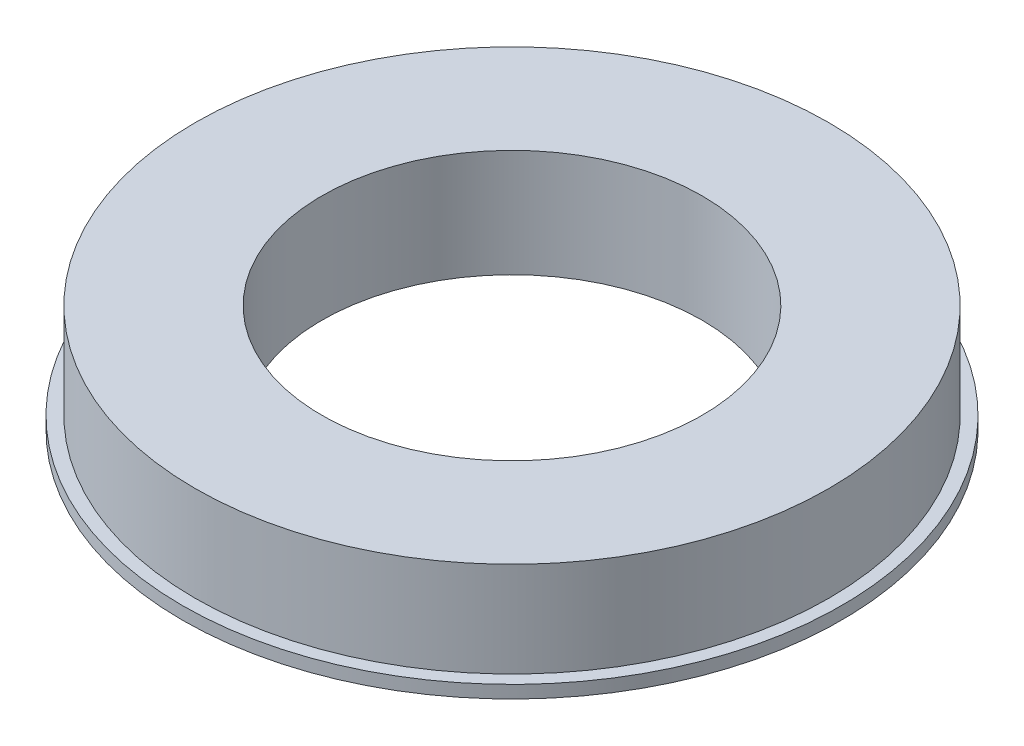
SolidWorks part; units mm, degrees
ref_plane "Front Plane" through (0, 0, 0) normal (0, 0, 1) x (1, 0, 0)
ref_plane "Top Plane" through (0, 0, 0) normal (0, 1, 0) x (1, 0, 0)
ref_plane "Right Plane" through (0, 0, 0) normal (1, 0, 0) x (0, 0, -1)
sketch "Sketch1" plane through (0, 0, 0) normal (0, 1, 0) x (1, 0, 0)
  circle A0 centre (0, 0) radius 66.04
  dimension "D1" = 132.08
extrude "Boss-Extrude1" add sketch "Sketch1" along normal blind 2.54
sketch "Sketch2" plane through (0, 2.54, 0) normal (0, 1, 0) x (1, 0, 0)
  circle A0 centre (0, 0) radius 63.5
  circle A2 centre (0, 0) radius 38.1
  dimension "D1" = 127
  dimension "D2" = 76.2
extrude "Boss-Extrude2" add sketch "Sketch2" along normal blind 19.05
sketch "Sketch3" plane through (0, 2.54, 0) normal (0, 1, 0) x (1, 0, 0)
  circle A1 centre (0, 0) radius 38.1
  circle A2 centre (0, 0) radius 38.1
  dimension "D1" = 0
extrude "Cut-Extrude1" cut sketch "Sketch3" against normal blind 10
